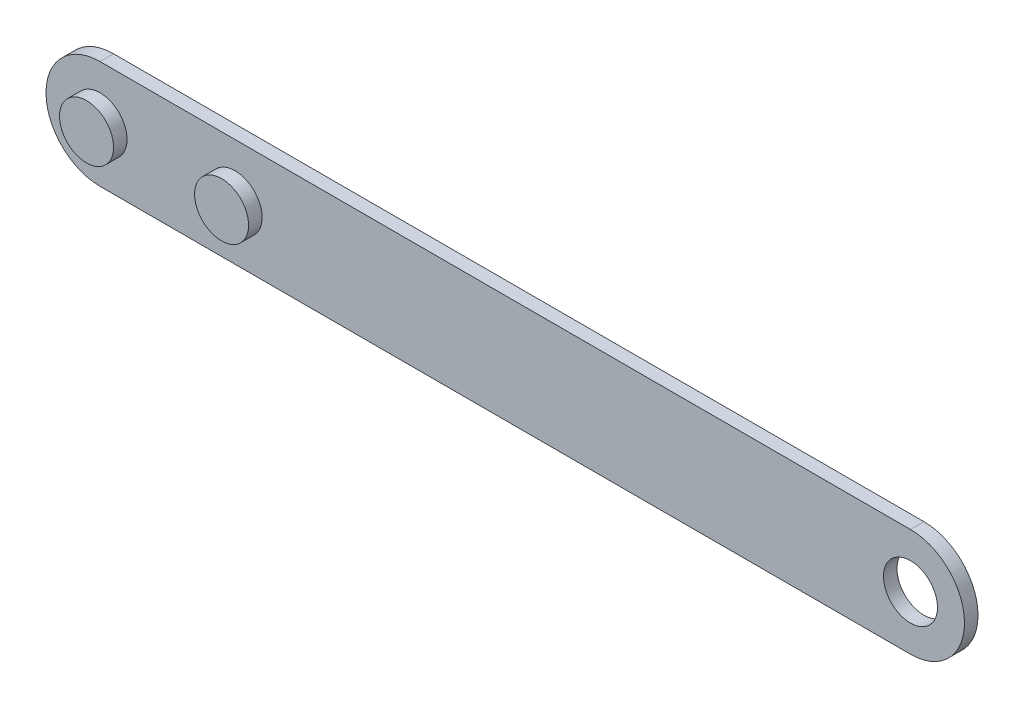
SolidWorks part; units mm, degrees
ref_plane "前视基准面" through (0, 0, 0) normal (0, 0, 1) x (1, 0, 0)
ref_plane "上视基准面" through (0, 0, 0) normal (0, 1, 0) x (1, 0, 0)
ref_plane "右视基准面" through (0, 0, 0) normal (1, 0, 0) x (0, 0, -1)
sketch "草图1" plane through (0, 0, 0) normal (0, 0, 1) x (1, 0, 0)
  line L0 (0, 0) -> (300, 0) construction
  line L1 (0, 20) -> (300, 20)
  line L2 (0, -20) -> (300, -20)
  arc A0 (0, 20) -> (0, -20) centre (0, 0) ccw
  arc A1 (300, -20) -> (300, 20) centre (300, 0) ccw
  circle A2 centre (300, 0) radius 10
  point P3 (150, 0)
  dimension "D2" = 20
  dimension "D3" = 20
  dimension "D1" = 300
extrude "凸台-拉伸1" add sketch "草图1" along normal blind 5
sketch "草图2" plane through (0, 0, 5) normal (0, 0, 1) x (1, 0, 0)
  line L0 (0, 0) -> (50, 0) construction
  circle A0 centre (0, 0) radius 10
  circle A1 centre (50, 0) radius 10
  dimension "D1" = 20
  dimension "D3" = 20
  dimension "D2" = 50
extrude "凸台-拉伸2" add sketch "草图2" along normal blind 5
